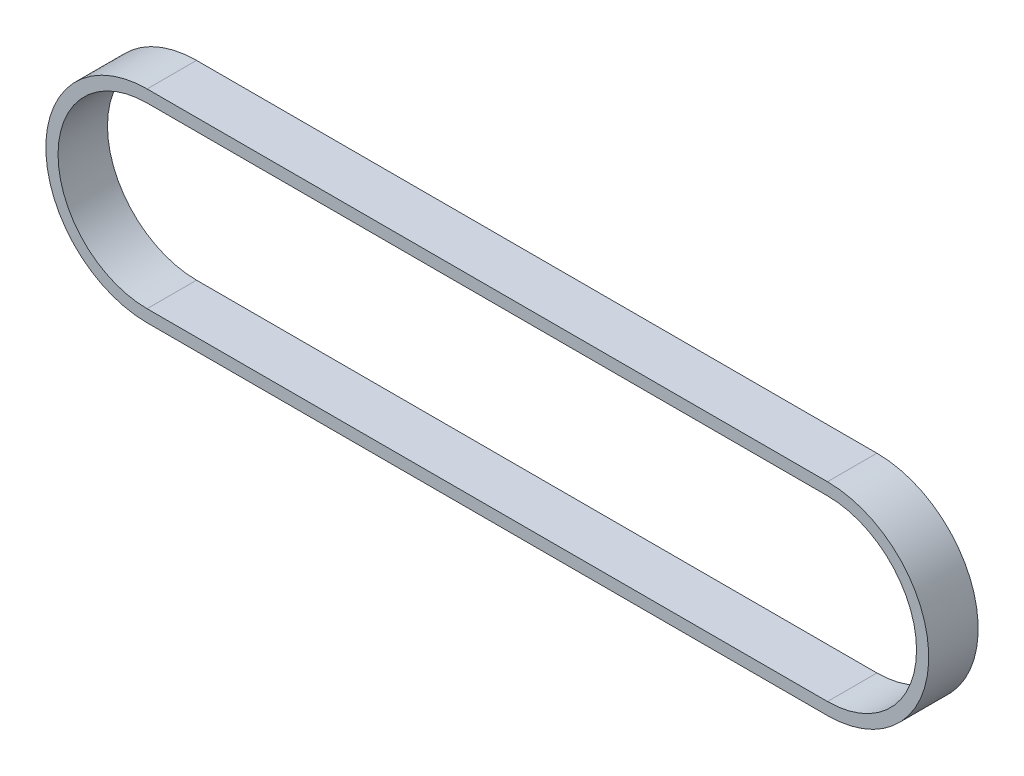
SolidWorks part; units mm, degrees
ref_plane "Plano frontal" through (0, 0, 0) normal (0, 0, 1) x (1, 0, 0)
ref_plane "Plano superior" through (0, 0, 0) normal (0, 1, 0) x (1, 0, 0)
ref_plane "Plano direito" through (0, 0, 0) normal (1, 0, 0) x (0, 0, -1)
sketch "Esboço1" plane through (0, 0, 0) normal (0, 0, 1) x (1, 0, 0)
  line L0 (0, 0) -> (131, 0) construction
  line L1 (0, 19.5) -> (131, 19.5)
  line L2 (0, -19.5) -> (131, -19.5)
  line L3 (0, 17.15) -> (131, 17.15)
  line L4 (0, -17.15) -> (131, -17.15)
  arc A0 (0, 19.5) -> (0, -19.5) centre (0, 0) ccw
  arc A1 (131, -19.5) -> (131, 19.5) centre (131, 0) ccw
  arc A2 (131, -17.15) -> (131, 17.15) centre (131, 0) ccw
  arc A3 (0, 17.15) -> (0, -17.15) centre (0, 0) ccw
  point P3 (65.5, 0)
  dimension "D1" = 19.5
  dimension "D2" = 131
  dimension "D3" = 2.35
extrude "Ressalto-extrusão1" add sketch "Esboço1" along normal blind 9.52
